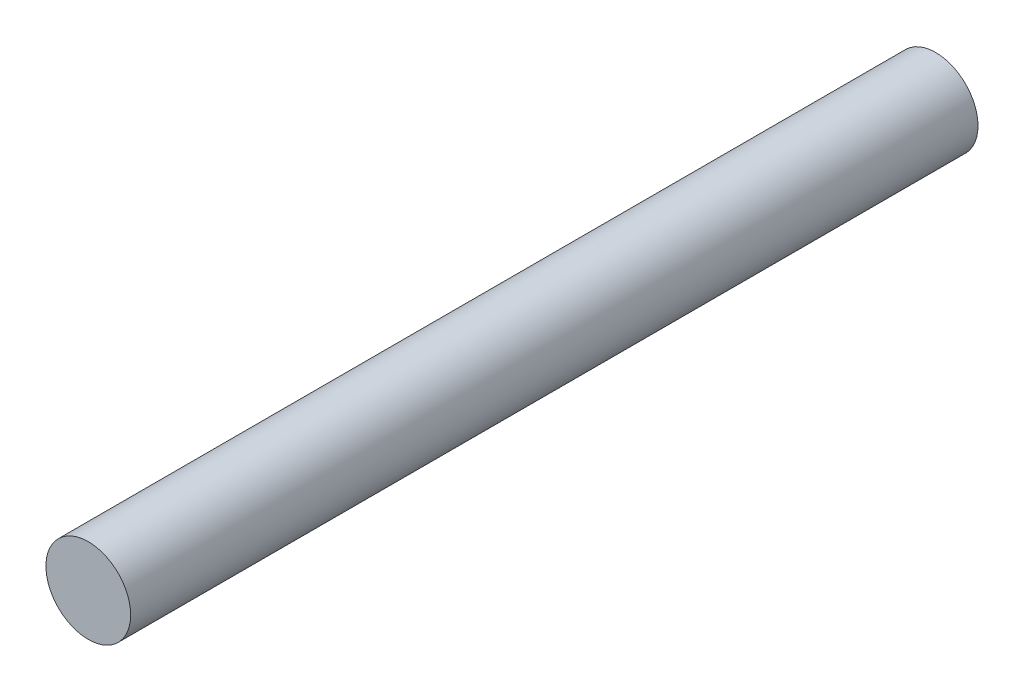
SolidWorks part; units mm, degrees
material "AISI 304"
ref_plane "前视基准面" through (0, 0, 0) normal (0, 0, 1) x (1, 0, 0)
ref_plane "上视基准面" through (0, 0, 0) normal (0, 1, 0) x (1, 0, 0)
ref_plane "右视基准面" through (0, 0, 0) normal (1, 0, 0) x (0, 0, -1)
sketch "草图1" plane through (0, 0, 0) normal (0, 0, 1) x (1, 0, 0)
  circle A0 centre (0, 0) radius 0.5
  dimension "D1" = 1
extrude "凸台-拉伸1" add sketch "草图1" along normal blind 10
